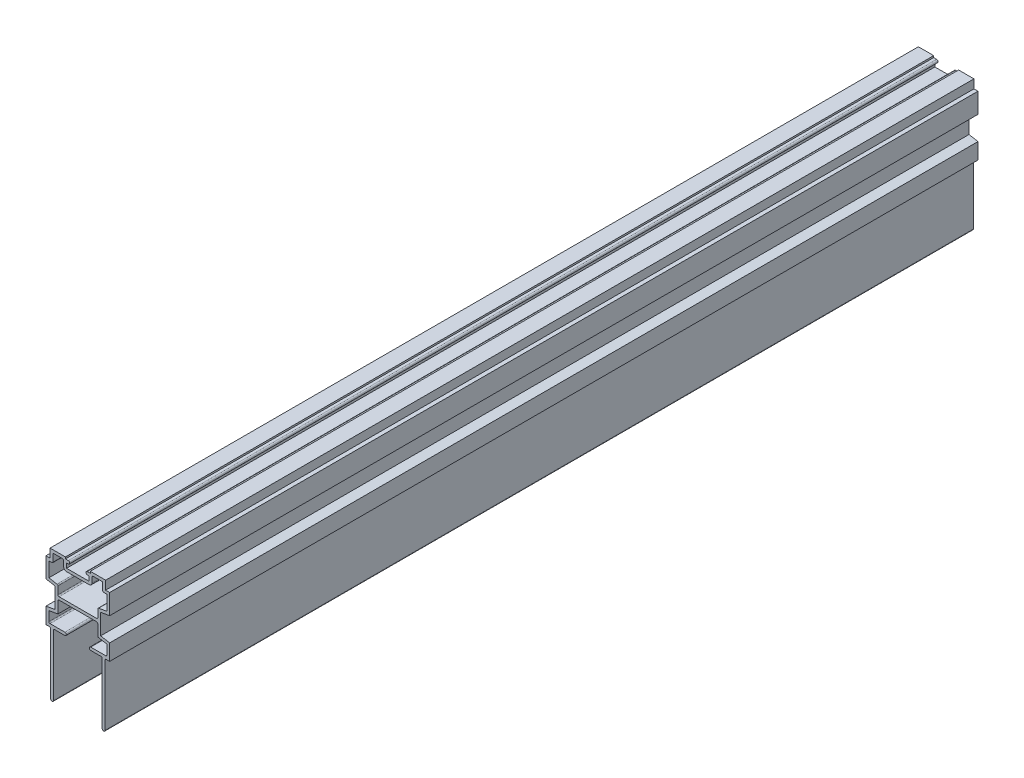
SolidWorks part; units mm, degrees
material "6063-T6"
ref_plane "Front Plane" through (0, 0, 0) normal (0, 0, 1) x (1, 0, 0)
ref_plane "Top Plane" through (0, 0, 0) normal (0, 1, 0) x (1, 0, 0)
ref_plane "Right Plane" through (0, 0, 0) normal (1, 0, 0) x (0, 0, -1)
sketch "Sketch1" plane through (0, 0, 0) normal (0, 0, 1) x (1, 0, 0)
  line L0 (0, -0.2928) -> (0, 7515.9895) construction
  line L1 (-3.9, 0) -> (3.9, 0)
  line L2 (3.9, 0) -> (3.9, 1.6)
  line L3 (3.9, 1.6) -> (3.3, 1.6)
  line L4 (4.3, 2.6) -> (4.3, 3.2)
  line L5 (3.3, 2.6) -> (4.3, 2.6)
  line L6 (4.3, 3.2) -> (9.6, 3.2)
  line L7 (9.6, 3.2) -> (9.6, 0.2)
  line L8 (9.6, 0.2) -> (11, 0.2)
  line L9 (11, 0.2) -> (11, -6.7307)
  line L10 (11, -6.7307) -> (7.8847, -7.28)
  line L11 (7.8847, -7.28) -> (7.8847, -14.32)
  line L12 (7.8847, -14.32) -> (11, -14.8693)
  line L13 (7.1847, -10.8) -> (-49992.8153, -10.8) construction
  line L14 (11, -20.4) -> (11, -14.8693)
  line L15 (11, -20.4) -> (9.8, -20.4)
  line L16 (9.4, -20.8) -> (9.4, -41.8)
  line L17 (0, -25.025) -> (0, 25.025) construction
  line L18 (-9.4, -20.8) -> (-9.4, -41.8)
  line L19 (-11, -20.4) -> (-9.8, -20.4)
  line L20 (-11, -20.4) -> (-11, -14.8693)
  line L21 (-7.8847, -14.32) -> (-11, -14.8693)
  line L22 (-7.8847, -7.28) -> (-7.8847, -14.32)
  line L23 (-11, -6.7307) -> (-7.8847, -7.28)
  line L24 (-11, 0.2) -> (-11, -6.7307)
  line L25 (-9.6, 0.2) -> (-11, 0.2)
  line L26 (-9.6, 3.2) -> (-9.6, 0.2)
  line L27 (-4.3, 3.2) -> (-9.6, 3.2)
  line L28 (-3.3, 2.6) -> (-4.3, 2.6)
  line L29 (-4.3, 2.6) -> (-4.3, 3.2)
  line L30 (-3.9, 1.6) -> (-3.3, 1.6)
  line L31 (-3.9, 0) -> (-3.9, 1.6)
  line L32 (-8.4, -20.8) -> (-8.4, -41.8)
  line L33 (-9.6, -19.4) -> (-8.4, -19.4)
  line L34 (-10, -19) -> (-10, -15.7084)
  line L35 (-6.8847, -15.1591) -> (-10, -15.7084)
  line L36 (-6.8847, -6.4409) -> (-6.8847, -9.4)
  line L37 (-10, -5.8916) -> (-6.8847, -6.4409)
  line L38 (-10, -0.8) -> (-10, -5.8916)
  line L39 (-8.6, -0.8) -> (-10, -0.8)
  line L40 (-8.6, 2.2) -> (-8.6, -0.8)
  line L41 (-5.3, 2.2) -> (-8.6, 2.2)
  line L42 (-5.3, 1.6) -> (-5.3, 2.2)
  line L43 (-4.9, 1.6) -> (-5.3, 1.6)
  line L44 (-4.9, 1.6) -> (-4.9, 1.6)
  line L45 (-4.9, -1) -> (-4.9, 1.6)
  line L46 (-4.9, -1) -> (4.9, -1)
  line L47 (4.9, -1) -> (4.9, 1.6)
  line L48 (4.9, 1.6) -> (4.9, 1.6)
  line L49 (4.9, 1.6) -> (5.3, 1.6)
  line L50 (5.3, 1.6) -> (5.3, 2.2)
  line L51 (5.3, 2.2) -> (8.6, 2.2)
  line L52 (8.6, 2.2) -> (8.6, -0.8)
  line L53 (8.6, -0.8) -> (10, -0.8)
  line L54 (10, -0.8) -> (10, -5.8916)
  line L55 (10, -5.8916) -> (6.8847, -6.4409)
  line L56 (6.8847, -6.4409) -> (6.8847, -9.4)
  line L57 (6.8847, -15.1591) -> (10, -15.7084)
  line L58 (10, -19) -> (10, -15.7084)
  line L59 (9.6, -19.4) -> (8.4, -19.4)
  line L60 (8.4, -20.8) -> (8.4, -41.8)
  line L61 (-8.4, -19.4) -> (-8.4, -41.8) construction
  line L62 (-8.4, -19.4) -> (-4.5, -19.4)
  line L64 (-8, -20.4) -> (-4.5, -20.4)
  line L66 (8, -20.4) -> (4.5, -20.4)
  line L67 (8.4, -19.4) -> (4.5, -19.4)
  line L68 (8.4, -19.4) -> (8.4, -41.8) construction
  line L69 (-6.8847, -11.2) -> (-6.8847, -15.1591)
  line L70 (-6.4847, -9.8) -> (6.4847, -9.8)
  line L72 (-6.4847, -10.8) -> (6.4847, -10.8)
  line L74 (-6.8847, -6.4409) -> (-6.8847, -15.1591) construction
  line L75 (6.8847, -11.2) -> (6.8847, -15.1591)
  line L76 (6.8847, -6.4409) -> (6.8847, -15.1591) construction
  line L77 (11, -20.4) -> (9.4, -20.4) construction
  line L78 (9.4, -20.4) -> (9.4, -41.8) construction
  line L79 (-9.4, -20.4) -> (-9.4, -41.8) construction
  line L80 (-11, -20.4) -> (-9.4, -20.4) construction
  line L81 (10, -19.4) -> (10, -15.7084) construction
  line L82 (10, -19.4) -> (8.4, -19.4) construction
  line L83 (-10, -19.4) -> (-8.4, -19.4) construction
  line L84 (-10, -19.4) -> (-10, -15.7084) construction
  arc A0 (3.3, 2.6) -> (3.3, 1.6) centre (3.3, 2.1) ccw
  arc A1 (-3.3, 2.6) -> (-3.3, 1.6) centre (-3.3, 2.1) cw
  arc A2 (-4.9, 1.6) -> (-4.9, 1.6) centre (-4.9, 1.6) ccw
  arc A3 (4.9, 1.6) -> (4.9, 1.6) centre (4.9, 1.6) cw
  arc A4 (-9.4, -41.8) -> (-8.4, -41.8) centre (-8.9, -41.8) ccw
  arc A5 (9.4, -41.8) -> (8.4, -41.8) centre (8.9, -41.8) cw
  arc A6 (-4.5, -19.4) -> (-4.5, -20.4) centre (-4.5, -19.9) cw
  arc A7 (4.5, -19.4) -> (4.5, -20.4) centre (4.5, -19.9) ccw
  arc A8 (9.8, -20.4) -> (9.4, -20.8) centre (9.8, -20.8) ccw
  arc A9 (-9.4, -20.8) -> (-9.8, -20.4) centre (-9.8, -20.8) ccw
  arc A10 (-8.4, -20.8) -> (-8, -20.4) centre (-8, -20.8) cw
  arc A11 (8, -20.4) -> (8.4, -20.8) centre (8, -20.8) cw
  arc A12 (10, -19) -> (9.6, -19.4) centre (9.6, -19) cw
  arc A13 (-9.6, -19.4) -> (-10, -19) centre (-9.6, -19) cw
  arc A14 (6.4847, -10.8) -> (6.8847, -11.2) centre (6.4847, -11.2) cw
  arc A15 (-6.8847, -11.2) -> (-6.4847, -10.8) centre (-6.4847, -11.2) cw
  arc A16 (6.4847, -9.8) -> (6.8847, -9.4) centre (6.4847, -9.4) ccw
  arc A17 (-6.4847, -9.8) -> (-6.8847, -9.4) centre (-6.4847, -9.4) cw
  point P20 (7.8847, -10.8)
  point P43 (0, 0)
  point P83 (-4, -19.9)
  point P95 (9.4, -20.4)
  point P99 (-9.4, -20.4)
  point P102 (-8.4, -20.4)
  point P105 (8.4, -20.4)
  point P114 (6.8847, -10.8)
  point P117 (-6.8847, -10.8)
  point P122 (-6.8847, -9.8)
  dimension "D22" = 1
  dimension "D23" = 0.4
  dimension "D1" = 3.9
  dimension "D2" = 1.6
  dimension "D3" = 1
  dimension "D4" = 0.6
  dimension "D5" = 1
  dimension "D6" = 0.6
  dimension "D7" = 5.3
  dimension "D8" = 3
  dimension "D9" = 1.4
  dimension "D10" = 7.04
  dimension "D11" = 20
  dimension "D12" = 10
  dimension "D13" = 14
  dimension "D14" = 11
  dimension "D15" = 0
  dimension "D16" = 23.6
  dimension "D17" = 1.6
  dimension "D18" = 21.4
  dimension "D19" = 45
  dimension "D21" = 4
  dimension "D20" = 1
extrude "Boss-Extrude1" add sketch "Sketch1" along normal blind 300
fillet "Fillet1" radius 1 2 edges at (-4.9, -1, 150) (4.9, -1, 150)
fillet "Fillet2" radius 0.3 5 edges at (8.6, -0.8, 150) (8.6, 2.2, 150) (-8.6, 2.2, 150) (-8.6, -0.8, 150) (-10, -0.8, 150)
sketch "Sketch3" plane through (0, 0, 0) normal (0, 0, -1) x (-1, 0, 0)
  line L1 (5.3, 1.6) -> (4.9, 1.6)
  line L2 (5.3, 1.6) -> (5.3, 2.2)
  line L3 (5.3, 2.2) -> (4.9, 2.2)
  line L4 (4.9, 1.6) -> (4.9, 2.2)
  line L5 (-5.3, 2.2) -> (-4.9, 2.2)
  line L6 (-5.3, 2.2) -> (-5.3, 1.6)
  line L7 (-5.3, 1.6) -> (-4.9, 1.6)
  line L8 (-4.9, 2.2) -> (-4.9, 1.6)
extrude "Cut-Extrude1" cut sketch "Sketch3" against normal blind 300
fillet "Fillet3" radius 0.4 4 edges at (4.9, 2.2, 150) (-4.9, 2.2, 150) (-6.8847, -6.4409, 150) (6.8847, -6.4409, 150)
